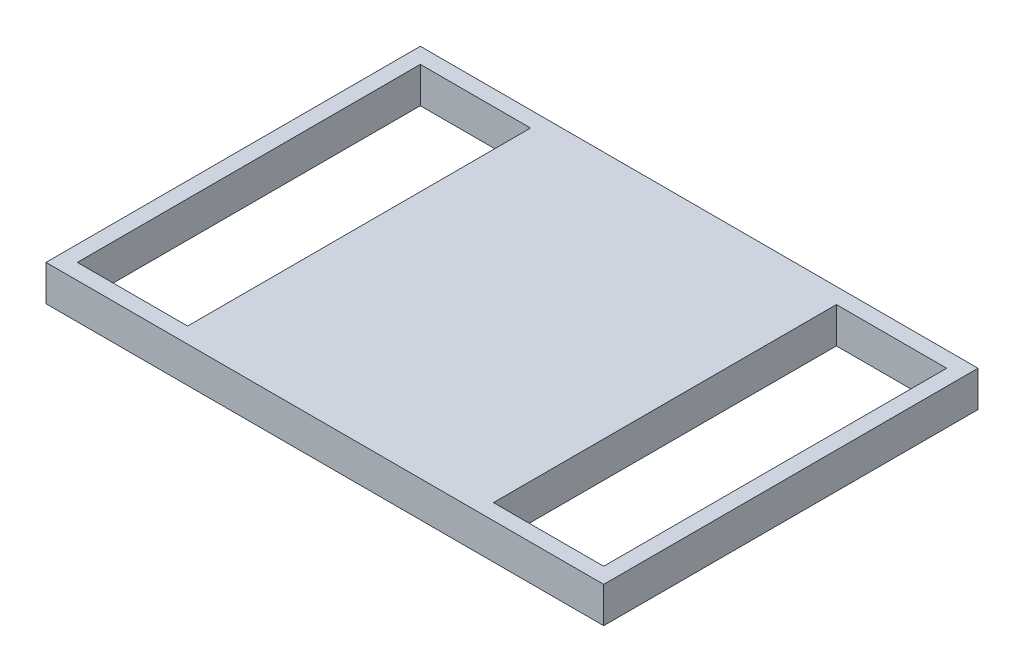
SolidWorks part; units mm, degrees
ref_plane "Front Plane" through (0, 0, 0) normal (0, 0, 1) x (1, 0, 0)
ref_plane "Top Plane" through (0, 0, 0) normal (0, 1, 0) x (1, 0, 0)
ref_plane "Right Plane" through (0, 0, 0) normal (1, 0, 0) x (0, 0, -1)
sketch "Sketch2" plane through (0, 0, 0) normal (0, 1, 0) x (1, 0, 0)
  line L0 (-147.5, 0) -> (147.5, 0) construction
  line L5 (-185, 195.2) -> (185, 195.2) construction
  line L6 (-197.7, -132.7) -> (197.7, -132.7)
  line L13 (110, 120) -> (185, 120)
  line L14 (110, 120) -> (110, -120)
  line L15 (110, -120) -> (185, -120)
  line L16 (185, 120) -> (185, -120)
  line L17 (110, 120) -> (185, -120) construction
  line L18 (110, -120) -> (185, 120) construction
  line L19 (-185, 120) -> (-110, 120)
  line L20 (-185, 120) -> (-185, -120)
  line L21 (-185, -120) -> (-110, -120)
  line L22 (-110, 120) -> (-110, -120)
  line L23 (-185, 120) -> (-110, -120) construction
  line L24 (-185, -120) -> (-110, 120) construction
  line L26 (-110, -37.5) -> (110, -37.5)
  line L27 (-110, -37.5) -> (-110, 37.5)
  line L28 (-110, 37.5) -> (110, 37.5)
  line L29 (110, -37.5) -> (110, 37.5)
  line L30 (-110, -37.5) -> (110, 37.5) construction
  line L31 (-110, 37.5) -> (110, -37.5) construction
  line L41 (-197.7, -132.7) -> (-197.7, 132.7)
  line L42 (-185, 132.7) -> (185, 132.7) construction
  line L43 (197.7, -132.7) -> (197.7, 132.7)
  line L44 (-197.7, -132.7) -> (197.7, 132.7) construction
  line L45 (-197.7, 132.7) -> (197.7, -132.7) construction
  line L47 (-197.7, 132.7) -> (-197.7, 257.7)
  line L48 (-197.7, 257.7) -> (-185, 257.7)
  line L49 (-185, 132.7) -> (-185, 257.7)
  line L51 (185, 132.7) -> (185, 257.7)
  line L52 (185, 257.7) -> (197.7, 257.7)
  line L53 (197.7, 132.7) -> (197.7, 257.7)
  line L54 (-185, 132.7) -> (185, 132.7)
  line L55 (223.1, 132.7) -> (223.1, 283.1)
  line L56 (159.6, 283.1) -> (223.1, 283.1)
  line L57 (159.6, 158.1) -> (159.6, 283.1)
  line L58 (-159.6, 158.1) -> (159.6, 158.1)
  line L59 (-159.6, 158.1) -> (-159.6, 283.1)
  line L60 (-223.1, 283.1) -> (-159.6, 283.1)
  line L61 (-223.1, 132.7) -> (-223.1, 283.1)
  line L62 (-223.1, -158.1) -> (-223.1, 132.7)
  line L63 (-223.1, -158.1) -> (223.1, -158.1)
  line L64 (223.1, -158.1) -> (223.1, 132.7)
  circle A0 centre (0, 308.1) radius 150
  point P2 (0, 0)
  point P13 (147.5, 0)
  point P18 (-147.5, 0)
  point P23 (0, 0)
  point P24 (0, 0)
  point P35 (0, 195.2)
  dimension "D1" = 300
  dimension "D2" = 75
  dimension "D3" = 240
  dimension "D4" = 75
  dimension "D5" = 220
  dimension "D6" = 12.7
  dimension "D7" = 12.7
  dimension "D8" = 12.7
  dimension "D9" = 125
  dimension "D10" = 25.4
sketch "Sketch5" plane through (0, 0, 0) normal (0, 1, 0) x (1, 0, 0)
  line L1 (197.7, -132.7) -> (-197.7, -132.7)
  line L2 (197.7, -132.7) -> (197.7, 132.7)
  line L3 (197.7, 132.7) -> (-197.7, 132.7)
  line L4 (-197.7, -132.7) -> (-197.7, 132.7)
extrude "Boss-Extrude3" add sketch "Sketch5" along normal blind 25.4
sketch "Sketch6" plane through (0, 25.4, 0) normal (0, 1, 0) x (1, 0, 0)
  line L0 (-185, 120) -> (-110, 120) construction
  line L1 (-185, 120) -> (-185, -120) construction
  line L2 (-185, -120) -> (-110, -120) construction
  line L3 (-110, 120) -> (-110, -120) construction
  line L4 (110, 120) -> (110, -120) construction
  line L5 (110, 120) -> (185, 120) construction
  line L6 (185, 120) -> (185, -120) construction
  line L7 (110, -120) -> (185, -120) construction
  line L8 (-185, 120) -> (-110, 120)
  line L9 (-185, 120) -> (-185, -120)
  line L10 (-185, -120) -> (-110, -120)
  line L11 (-110, 120) -> (-110, -120)
  line L12 (110, 120) -> (110, -120)
  line L13 (110, 120) -> (185, 120)
  line L14 (185, 120) -> (185, -120)
  line L15 (110, -120) -> (185, -120)
  line L16 (108.4125, 121.5875) -> (108.4125, -121.5875)
  line L17 (108.4125, -121.5875) -> (186.5875, -121.5875)
  line L18 (186.5875, 121.5875) -> (186.5875, -121.5875)
  line L19 (108.4125, 121.5875) -> (186.5875, 121.5875)
  line L20 (-108.4125, 121.5875) -> (-108.4125, -121.5875)
  line L21 (-186.5875, -121.5875) -> (-108.4125, -121.5875)
  line L22 (-186.5875, 121.5875) -> (-186.5875, -121.5875)
  line L23 (-186.5875, 121.5875) -> (-108.4125, 121.5875)
  dimension "D1" = 1.5875
extrude "Cut-Extrude1" cut sketch "Sketch6" against normal through all contours L12 L15 L14 L13 | L19 L16 L17 L18 L15 L12 L13 L14 | L11 L8 L9 L10 | L23 L22 L21 L20 L8 L11 L10 L9
